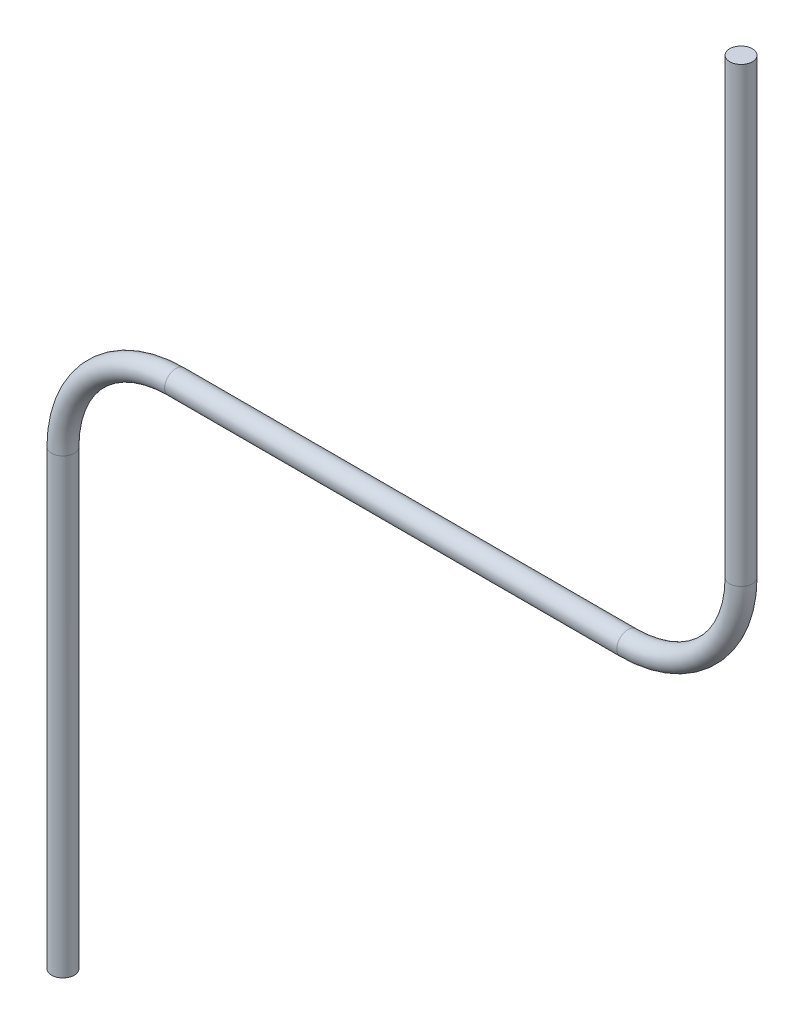
SolidWorks part; units mm, degrees
ref_plane "Front Plane" through (0, 0, 0) normal (0, 0, 1) x (1, 0, 0)
ref_plane "Top Plane" through (0, 0, 0) normal (0, 1, 0) x (1, 0, 0)
ref_plane "Right Plane" through (0, 0, 0) normal (1, 0, 0) x (0, 0, -1)
sketch "Sketch1" plane through (0, 0, 0) normal (0, 0, -1) x (1, 0, 0)
  line L0 (0, 0) -> (0, 80)
  line L1 (-20, 100) -> (-100, 100)
  line L2 (-120, 120) -> (-120, 200)
  arc A0 (-120, 120) -> (-100, 100) centre (-100, 120) ccw
  arc A1 (0, 80) -> (-20, 100) centre (-20, 80) ccw
  point P9 (0, 100)
  dimension "D2" = 20
  dimension "D1" = 100
sketch "Sketch2" plane through (0, 0, 0) normal (0, 1, 0) x (1, 0, 0)
  circle A0 centre (0, 0) radius 2
  dimension "D1" = 4
sweep "Sweep1" add profiles "Sketch2" path "Sketch1"
